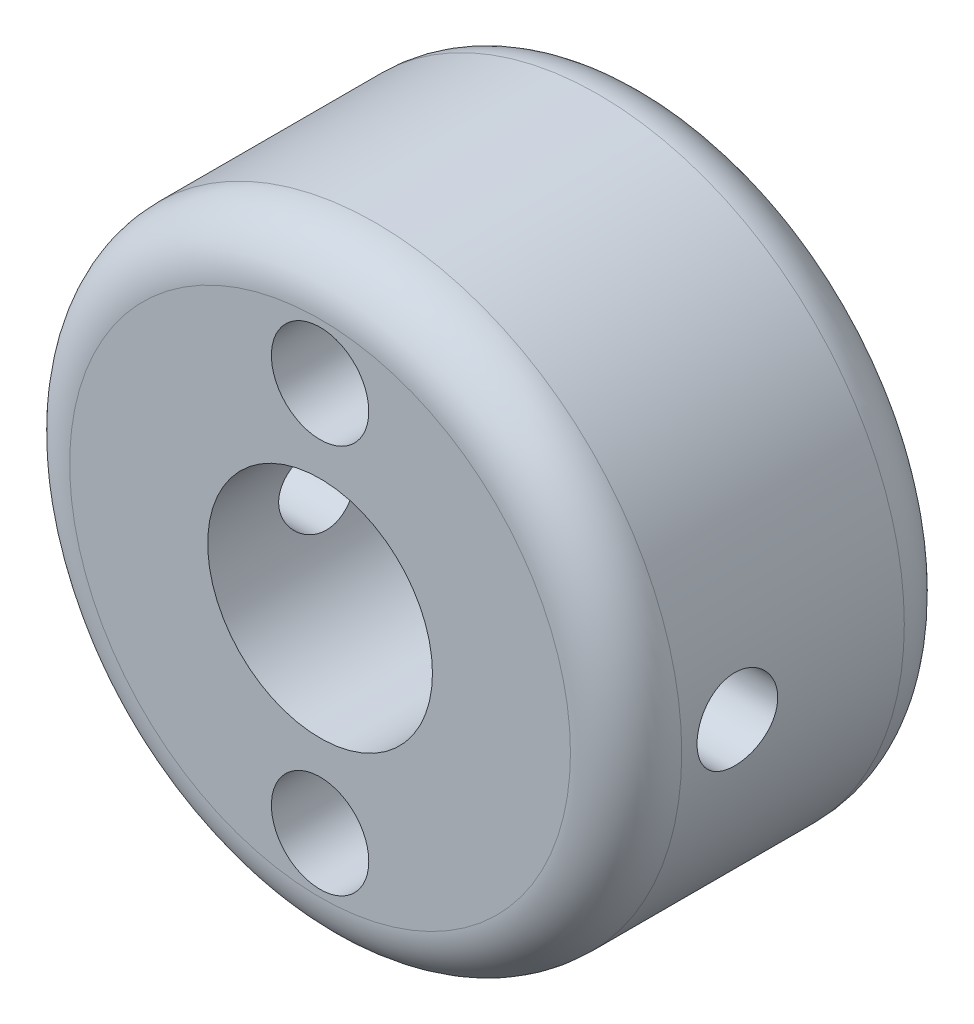
SolidWorks part; units mm, degrees
ref_plane "前视基准面" through (0, 0, 0) normal (0, 0, 1) x (1, 0, 0)
ref_plane "上视基准面" through (0, 0, 0) normal (0, 1, 0) x (1, 0, 0)
ref_plane "右视基准面" through (0, 0, 0) normal (1, 0, 0) x (0, 0, -1)
sketch "草图1" plane through (0, 0, 0) normal (0, 0, 1) x (1, 0, 0)
  circle A0 centre (0, 0) radius 11
  dimension "D1" = 22
extrude "凸台-拉伸1" add sketch "草图1" along normal blind 12
sketch "草图3" plane through (0, 0, 12) normal (0, 0, 1) x (1, 0, 0)
  circle A0 centre (0, 7) radius 1.75
  circle A1 centre (0, -7) radius 1.75
  dimension "D1" = 3.5
  dimension "D2" = 14
extrude "切除-拉伸1" cut sketch "草图3" against normal through all
sketch "草图4" plane through (0, 0, 12) normal (0, 0, 1) x (1, 0, 0)
  circle A0 centre (0, 0) radius 4.04
  dimension "D1" = 8.08
extrude "切除-拉伸2" cut sketch "草图4" against normal offset from surface (10 mm away) 2 up to face at (1.75, 7, 0)
sketch "草图5" plane through (0, 0, 0) normal (1, 0, 0) x (0, 0, -1)
  line L0 (-12, 11) -> (-12, -11) construction
  circle A0 centre (-8, 0) radius 1.45
  circle A1 centre (-2, 0) radius 1.45 construction
  dimension "D1" = 2.9
  dimension "D2" = 4
  dimension "D4" = 6
  dimension "D3" = 2
extrude "切除-拉伸3" cut sketch "草图5" against normal through all both and the other way through all
fillet "圆角1" radius 2 2 edges at (11, 0, 0) (11, 0, 12)
equation "\"4。5\"=4.3802"
